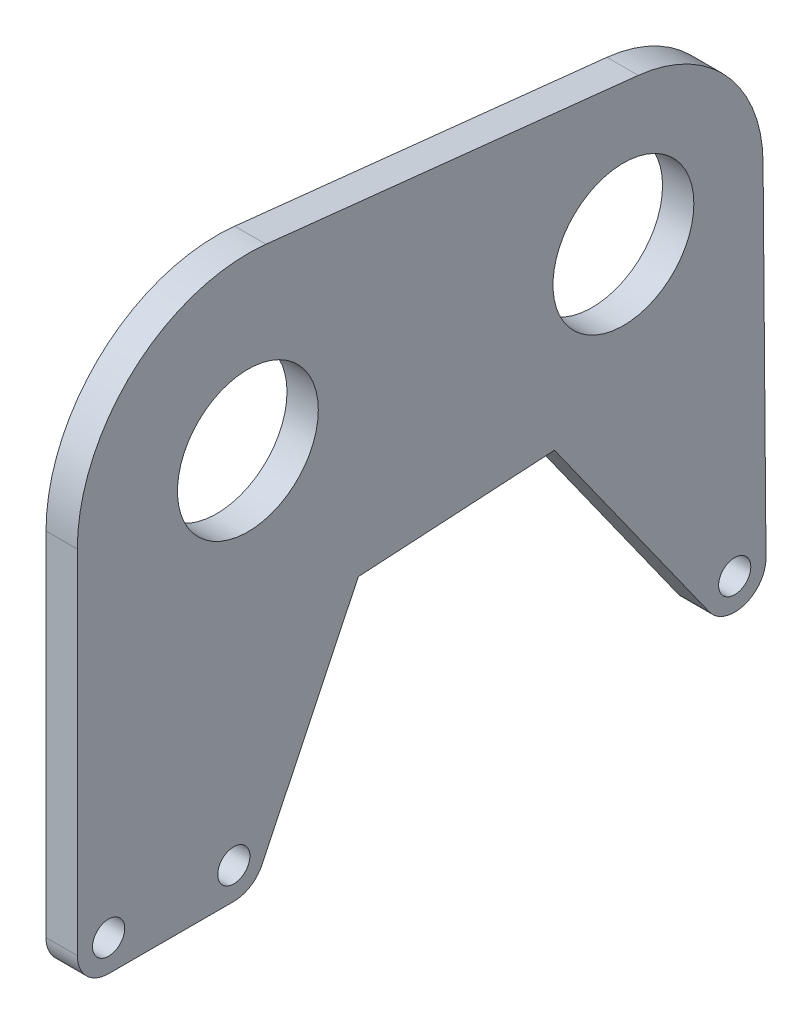
SolidWorks part; units mm, degrees
material "6061-T6 (SS)"
ref_plane "Front Plane" through (0, 0, 0) normal (0, 0, 1) x (1, 0, 0)
ref_plane "Top Plane" through (0, 0, 0) normal (0, 1, 0) x (1, 0, 0)
ref_plane "Right Plane" through (0, 0, 0) normal (1, 0, 0) x (0, 0, -1)
sketch "Sketch2" plane through (0, 0, 0) normal (1, 0, 0) x (0, 0, -1)
  line L0 (52.1431, -103.1833) -> (153.7431, -103.1833) construction
  line L1 (52.1431, -103.1833) -> (26.7431, -103.1833) construction
  line L2 (102.9431, -103.1833) -> (102.9431, -90.4833) construction
  line L3 (20.3931, -31.75) -> (20.3931, -103.1833)
  line L4 (26.7431, -109.5333) -> (52.1431, -109.5333)
  line L5 (57.8716, -105.923) -> (86.2061, -46.6781)
  line L6 (58.6768, 2.6528) -> (134.1867, -5.4335)
  line L7 (57.0007, -66.2912) -> (132.8143, -61.8837)
  line L8 (108.0949, -50.0366) -> (148.5708, -106.8671)
  line L9 (159.4986, -33.3607) -> (160.0928, -103.1292)
  line L10 (52.1431, -109.5333) -> (153.7431, -109.5333)
  circle A0 centre (102.9431, -90.4833) radius 14.2875 construction
  circle A1 centre (131.1701, -33.602) radius 14.2875 construction
  circle A2 centre (54.9926, -31.75) radius 14.2875 construction
  circle A3 centre (102.9431, -90.4833) radius 14.2875
  circle A4 centre (131.1701, -33.602) radius 14.2875
  circle A5 centre (54.9926, -31.75) radius 14.2875
  circle A6 centre (52.1431, -103.1833) radius 3.2639
  circle A7 centre (52.1431, -103.1833) radius 6.35
  circle A8 centre (153.7431, -103.1833) radius 3.2639
  circle A9 centre (153.7431, -103.1833) radius 6.35
  circle A10 centre (26.7431, -103.1833) radius 3.2639
  circle A11 centre (26.7431, -103.1833) radius 6.35
  circle A12 centre (54.9926, -31.75) radius 34.5995
  circle A13 centre (131.1701, -33.602) radius 28.3295
  dimension "D1" = 6.5278
  dimension "D2" = 12.7
  dimension "D3" = 25.4
  dimension "D4" = 101.6
  dimension "D5" = 12.7
extrude "Boss-Extrude2" add sketch "Sketch2" along normal blind 6.35 contours A12 A5 | A12 L3 A11 L4 A7 L5 L7 | A7 A6 | A11 A10 | A13 A4 | A13 L6 A12 L5 L7 L8 | A12 L7 L5 | A13 L8 L7 | A13 L7 L8 A9 L9 | A9 A8
